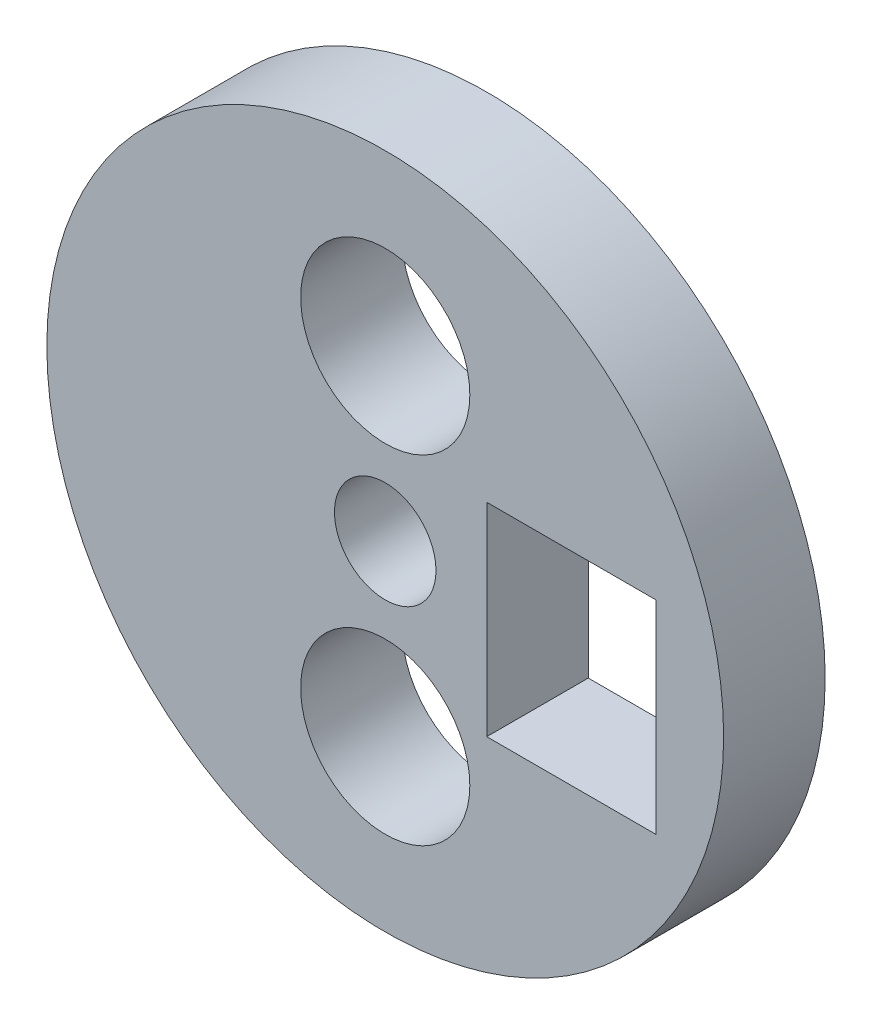
SolidWorks part; units mm, degrees
ref_plane "Front Plane" through (0, 0, 0) normal (0, 0, 1) x (1, 0, 0)
ref_plane "Top Plane" through (0, 0, 0) normal (0, 1, 0) x (1, 0, 0)
ref_plane "Right Plane" through (0, 0, 0) normal (1, 0, 0) x (0, 0, -1)
sketch "Sketch1" plane through (0, 0, 0) normal (0, 0, 1) x (1, 0, 0)
  circle A0 centre (0, 0) radius 10
  circle A1 centre (0, 5) radius 2.5
  circle A2 centre (0, 0) radius 1.5
  circle A3 centre (0, -5) radius 2.5
  point P8 (0, 0)
  dimension "D1" = 20
  dimension "D2" = 3
  dimension "D3" = 5
  dimension "D4" = 5
  dimension "D5" = 5
extrude "Boss-Extrude1" add sketch "Sketch1" along normal blind 3
sketch "Sketch2" plane through (0, 0, 3) normal (0, 0, 1) x (1, 0, 0)
  line L1 (3, 2.5) -> (8, 2.5)
  line L2 (3, 2.5) -> (3, -3.5)
  line L3 (3, -3.5) -> (8, -3.5)
  line L4 (8, 2.5) -> (8, -3.5)
  circle A0 centre (0, 0) radius 1.5 construction
  dimension "D4" = 3
  dimension "D1" = 5
  dimension "D2" = 6
  dimension "D3" = 2.5
extrude "Cut-Extrude1" cut sketch "Sketch2" against normal blind 3
